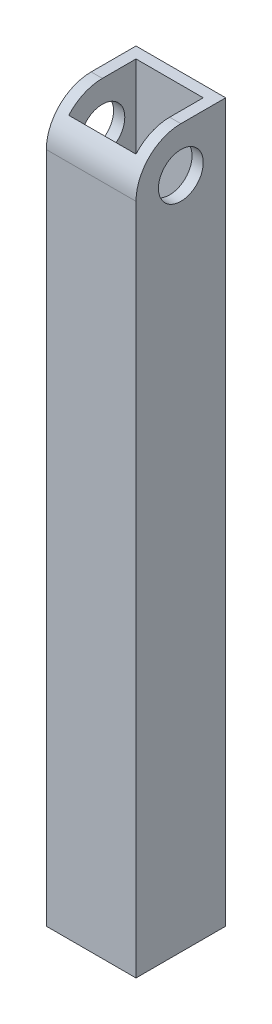
SolidWorks part; units mm, degrees
material "1060 Alloy"
ref_plane "Front Plane" through (0, 0, 0) normal (0, 0, 1) x (1, 0, 0)
ref_plane "Top Plane" through (0, 0, 0) normal (0, 1, 0) x (1, 0, 0)
ref_plane "Right Plane" through (0, 0, 0) normal (1, 0, 0) x (0, 0, -1)
sketch "Sketch1" plane through (0, 0, 0) normal (0, 1, 0) x (1, 0, 0)
  line L1 (-12.7, -12.7) -> (12.7, -12.7)
  line L2 (-12.7, -12.7) -> (-12.7, 12.7)
  line L3 (-12.7, 12.7) -> (12.7, 12.7)
  line L4 (12.7, -12.7) -> (12.7, 12.7)
  line L5 (-12.7, -12.7) -> (12.7, 12.7) construction
  line L6 (-12.7, 12.7) -> (12.7, -12.7) construction
  point P0 (0, 0)
  dimension "D1" = 25.4
extrude "Extrude-Thin1" add sketch "Sketch1" along normal blind 203.2 thin thin type one direction reverse wall 3.175
sketch "Sketch2" plane through (12.7, 0, 0) normal (1, 0, 0) x (0, 0, -1)
  line L0 (-12.7, 203.2) -> (12.7, 203.2) construction
  circle A0 centre (0, 190.5) radius 6.35
  point P5 (0, 203.2)
  dimension "D1" = 12.7
  dimension "D2" = 12.7
extrude "Cut-Extrude1" cut sketch "Sketch2" against normal through all
sketch "Sketch3" [suppressed] plane through (0, 0, -12.7) normal (0, 0, -1) x (-1, 0, 0)
  line L0 (-12.7, 0) -> (12.7, 0) construction
  circle A0 centre (0, 12.7) radius 6.35
  dimension "D1" = 12.7
  dimension "D2" = 12.7
extrude "Cut-Extrude2" [suppressed] cut sketch "Sketch3" against normal through all
sketch "Sketch4" plane through (12.7, 0, 0) normal (1, 0, 0) x (0, 0, -1)
  line L0 (-12.7, 203.2) -> (12.7, 203.2) construction
  line L1 (-12.7, 203.2) -> (-12.7, 0) construction
  line L2 (0, 190.5) -> (-12.7, 190.5) construction
  line L3 (-12.7, 190.5) -> (-12.7, 203.2)
  line L4 (-12.7, 203.2) -> (0, 203.2)
  arc A0 (0, 203.2) -> (-12.7, 190.5) centre (0, 190.5) ccw
extrude "Cut-Extrude3" cut sketch "Sketch4" against normal through all
